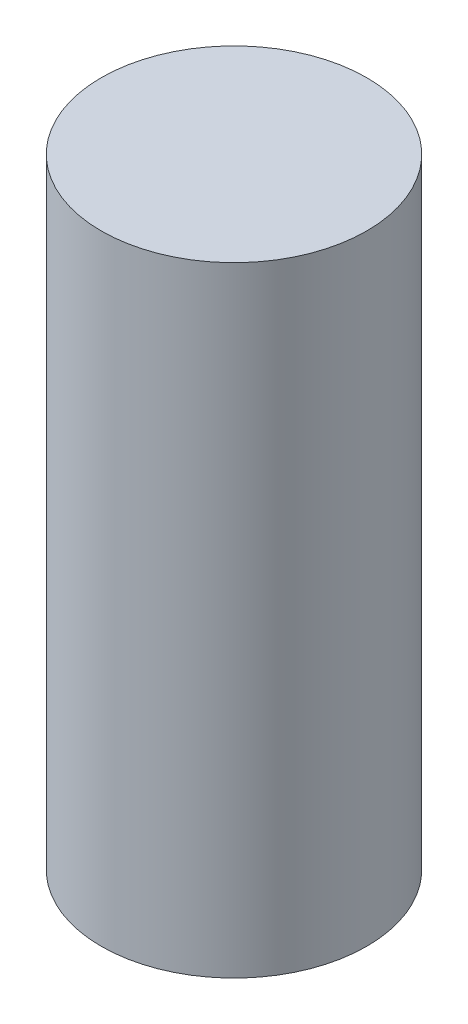
SolidWorks part; units mm, degrees
ref_plane "Front Plane" through (0, 0, 0) normal (0, 0, 1) x (1, 0, 0)
ref_plane "Top Plane" through (0, 0, 0) normal (0, 1, 0) x (1, 0, 0)
ref_plane "Right Plane" through (0, 0, 0) normal (1, 0, 0) x (0, 0, -1)
other "Configuration Table"
sketch "Sketch1" plane through (0, 0, 0) normal (0, 1, 0) x (1, 0, 0)
  circle A0 centre (50, 50) radius 6
extrude "OVEN_ayar_mil_1" add sketch "Sketch1" along normal blind 28 from offset 12 separate body
